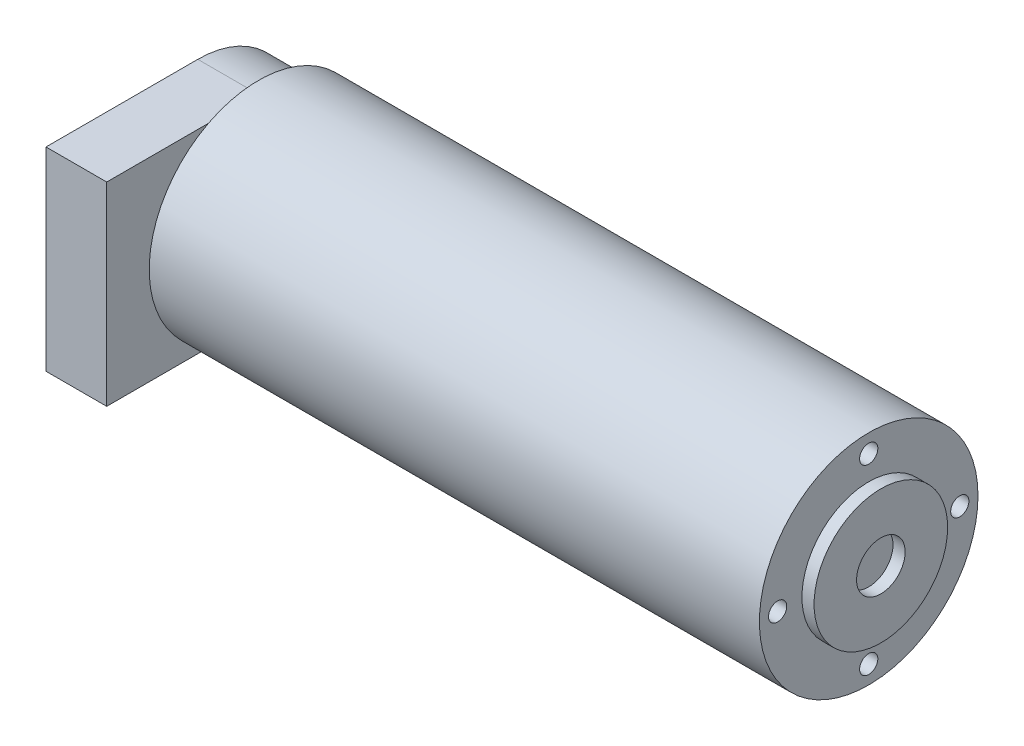
SolidWorks part; units mm, degrees
ref_plane "前视基准面" through (0, 0, 0) normal (0, 0, 1) x (1, 0, 0)
ref_plane "上视基准面" through (0, 0, 0) normal (0, 1, 0) x (1, 0, 0)
ref_plane "右视基准面" through (0, 0, 0) normal (1, 0, 0) x (0, 0, -1)
other "Configuration Table"
sketch "草图2" plane through (0, 0, 0) normal (1, 0, 0) x (0, 0, -1)
  circle A0 centre (0, 0) radius 18
extrude "凸台-拉伸1" add sketch "草图2" along normal blind 110.5 contours A0
sketch "草图3" plane through (110.5, 0, 0) normal (1, 0, 0) x (0, 0, -1)
  circle A0 centre (0, 0) radius 11
extrude "凸台-拉伸2" add sketch "草图3" along normal blind 2
sketch "草图4" plane through (112.5, 0, 0) normal (1, 0, 0) x (0, 0, -1)
  circle A0 centre (0, 0) radius 4
extrude "凸台-拉伸3" add sketch "草图4" along normal blind 15 contours A0
sketch "草图5" plane through (0, 0, 0) normal (-1, 0, 0) x (0, 0, 1)
  line L1 (0, 16) -> (25, 16)
  line L2 (0, 16) -> (0, -16)
  line L3 (0, -16) -> (25, -16)
  line L4 (25, 16) -> (25, -16)
  circle A0 centre (0, 0) radius 16
  circle M6 centre (0, 0) radius 18
  dimension "D1" = 25
extrude "凸台-拉伸4" add sketch "草图5" along normal blind 19 contours L4 L1 L3 M6 | L2 A0 | L2 A0 | A0 L3 L1 M6
sketch "草图6" plane through (127.5, 0, 0) normal (1, 0, 0) x (0, 0, -1)
  circle A0 centre (0, 0) radius 4
extrude "切除-拉伸2" cut sketch "草图6" against normal blind 17
sketch "草图8" plane through (110.5, 0, 0) normal (1, 0, 0) x (0, 0, -1)
  line L0 (0, -21.1268) -> (0, 21.1268) construction
  line L1 (-32.1386, 0) -> (32.1386, 0) construction
  line L2 (22.1921, -22.1921) -> (-22.1921, 22.1921) construction
  line L3 (-23.8185, -23.8185) -> (23.8185, 23.8185) construction
  circle A0 centre (0, 0) radius 15
  circle A1 centre (0, 15) radius 1.5
  circle A2 centre (15, 0) radius 1.5
  circle A3 centre (0, -15) radius 1.5
  circle A4 centre (-15, 0) radius 1.5
  point P6 (0, 0)
  point P9 (0, 0)
  point P12 (0, 0)
  point P15 (0, 0)
extrude "切除-拉伸3" cut sketch "草图8" against normal blind 8 contours A0 A1 | A0 A1 | A0 A2 | A0 A2 | A3 A0 | A3 A0 | A4 A0 | A4 A0
sketch "草图9" plane through (0, -16, 0) normal (0, -1, 0) x (1, 0, 0)
  line L1 (-19, 25) -> (-12, 25)
  line L2 (-19, 25) -> (-19, -28.664)
  line L3 (-19, -28.664) -> (-12, -28.664)
  line L4 (-12, 25) -> (-12, -28.664)
  dimension "D1" = 7
extrude "切除-拉伸4" cut sketch "草图9" against normal through all
sketch "草图10" plane through (0, -16, 0) normal (0, -1, 0) x (1, 0, 0)
  line L1 (-12, 25) -> (-10, 25)
  line L2 (-12, 25) -> (-12, -27.1333)
  line L3 (-12, -27.1333) -> (-10, -27.1333)
  line L4 (-10, 25) -> (-10, -27.1333)
  dimension "D1" = 2
extrude "切除-拉伸6" cut sketch "草图10" against normal through all contours L2 L1 L4 L3
sketch "草图11" plane through (-10, 0, 0) normal (-1, 0, 0) x (0, 0, 1)
  line L0 (0, 16) -> (25, 16) construction
  line L1 (25, 16) -> (0, 16)
  line L2 (25, 16) -> (25, -16)
  line L3 (25, -16) -> (0, -16)
  line L4 (0, 16) -> (0, -16)
  line L5 (25, 16) -> (25, -16) construction
  circle A0 centre (0, 0) radius 16
  arc M6 (0, 16) -> (0, -16) centre (0, 0) ccw
  line M7 (0, -16) -> (25, -16)
  line M8 (25, -16) -> (25, 16)
  line M9 (25, 16) -> (0, 16)
extrude "凸台-拉伸5" add sketch "草图11" against normal blind 20 contours A0 M7 M8 M9 | L4 M6 | L4 A0
sketch "草图12" plane through (0, 0, 0) normal (-1, 0, 0) x (0, 0, 1)
  circle A0 centre (0, 0) radius 16
  circle A1 centre (0, 0) radius 18
extrude "切除-拉伸7" cut sketch "草图12" along normal blind 20
sketch "草图13" plane through (-10, 0, 0) normal (-1, 0, 0) x (0, 0, 1)
  line L1 (25, 16) -> (0, 16)
  line L2 (25, 16) -> (25, -16)
  line L3 (25, -16) -> (0, -16)
  line L4 (0, 16) -> (0, -16)
  circle A0 centre (0, 0) radius 16 construction
  circle A1 centre (0, 0) radius 16 construction
extrude "凸台-拉伸6" add sketch "草图13" against normal blind 20
sketch "草图14" plane through (0, 0, 25) normal (0, 0, 1) x (1, 0, 0)
  line L0 (-10, 16) -> (10, 16) construction
  line L1 (0, 16) -> (-10, 16)
  line L2 (0, 16) -> (0, -16)
  line L3 (0, -16) -> (-10, -16)
  line L4 (-10, 16) -> (-10, -16)
extrude "切除-拉伸8" cut sketch "草图14" against normal through all
sketch "草图15" plane through (0, 0, 0) normal (-1, 0, 0) x (0, 0, 1)
  circle A1 centre (0, 0) radius 18
extrude "切除-拉伸10" cut sketch "草图15" against normal blind 10
sketch "草图16" plane through (10, 0, 0) normal (-1, 0, 0) x (0, 0, 1)
  circle A0 centre (0, 0) radius 16
extrude "凸台-拉伸7" add sketch "草图16" along normal blind 10
sketch "草图17" plane through (0, 0, 0) normal (-1, 0, 0) x (0, 0, 1)
  line L1 (25, 16) -> (0, 16)
  line L2 (25, 16) -> (25, -16)
  line L3 (25, -16) -> (0, -16)
  line L4 (0, 16) -> (0, -16)
  circle A0 centre (0, 0) radius 16 construction
  circle A1 centre (0, 0) radius 16 construction
extrude "凸台-拉伸8" add sketch "草图17" against normal blind 10
